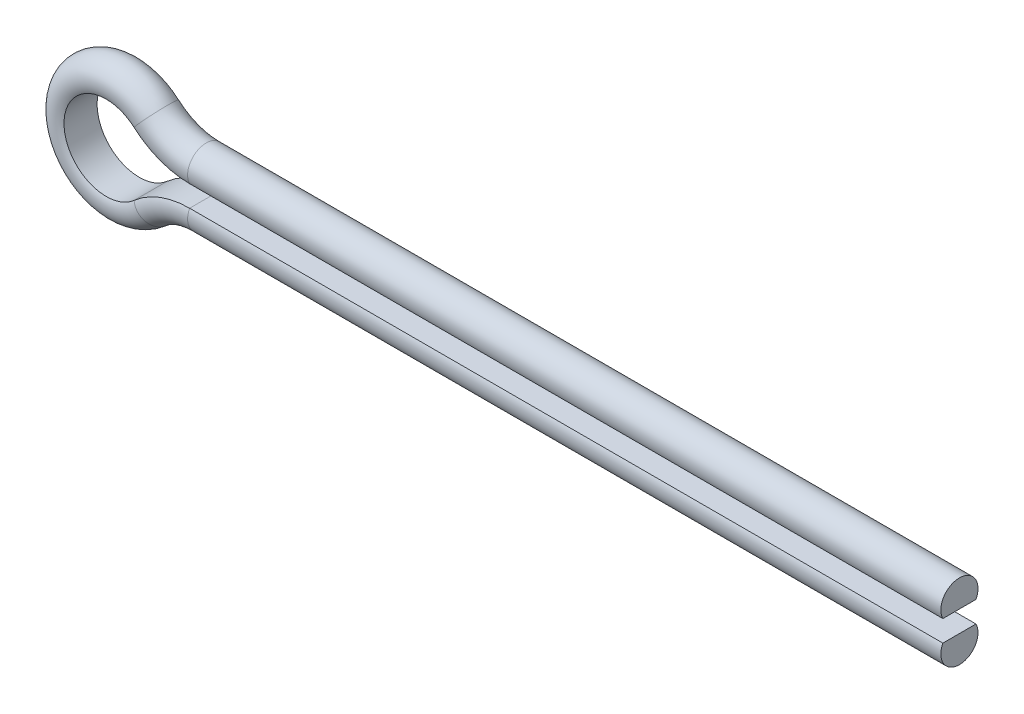
SolidWorks part; units mm, degrees
ref_plane "Front Plane" through (0, 0, 0) normal (0, 0, 1) x (1, 0, 0)
ref_plane "Top Plane" through (0, 0, 0) normal (0, 1, 0) x (1, 0, 0)
ref_plane "Right Plane" through (0, 0, 0) normal (1, 0, 0) x (0, 0, -1)
sketch "Sketch1" plane through (0, 0, 0) normal (0, 0, 1) x (1, 0, 0)
  line L0 (-209.0864, -15.2337) -> (1201.7779, -15.2337) construction
  line L2 (956.9409, -27.7337) -> (61.4743, -27.7337)
  line L3 (956.9409, -2.7337) -> (61.4743, -2.7337)
  arc A0 (-4.6694, 22.2663) -> (-4.6694, -52.7337) centre (-37.7413, -15.2337) ccw
  arc A2 (-4.6694, 22.2663) -> (61.4743, -2.7337) centre (61.4743, 97.2663) ccw
  arc A3 (-4.6694, -52.7337) -> (61.4743, -27.7337) centre (61.4743, -127.7337) cw
ref_plane "Plane1" through (956.9409, -2.7337, 0) normal (-1, 0, 0) x (0, 0, 1)
sketch "Sketch2" plane through (956.9409, -2.7337, 0) normal (-1, 0, 0) x (0, 0, 1)
  line L1 (19.6976, 0.126) -> (-19.6976, 0.126)
  line L5 (0, -62.5) -> (0, 37.5) construction
  arc A1 (19.6976, 0.126) -> (-19.6976, 0.126) centre (0, 10.126) ccw
  point P3 (0, 0.126)
  point P4 (0, 0)
sweep "Sweep3" add profiles "Sketch2" path "Sketch1"
